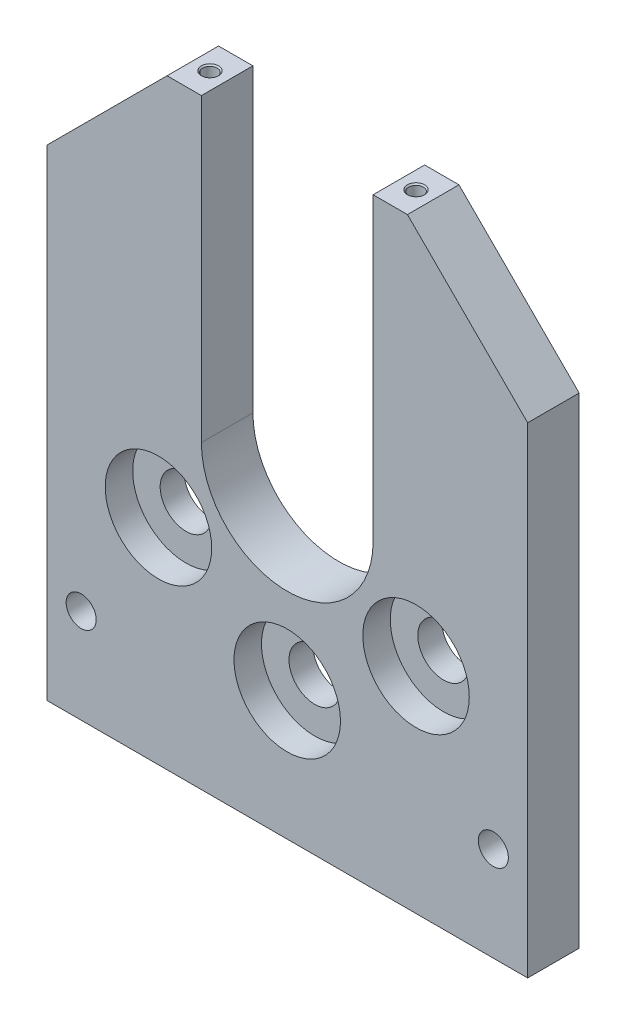
SolidWorks part; units mm, degrees
ref_plane "Front Plane" through (0, 0, 0) normal (0, 0, 1) x (1, 0, 0)
ref_plane "Top Plane" through (0, 0, 0) normal (0, 1, 0) x (1, 0, 0)
ref_plane "Right Plane" through (0, 0, 0) normal (1, 0, 0) x (0, 0, -1)
sketch "Sketch1" plane through (0, 0, 0) normal (0, 1, 0) x (1, 0, 0)
  line L1 (-140, 15) -> (140, 15)
  line L2 (-140, 15) -> (-140, -15)
  line L3 (-140, -15) -> (140, -15)
  line L4 (140, 15) -> (140, -15)
  line L5 (-140, 15) -> (140, -15) construction
  line L6 (-140, -15) -> (140, 15) construction
  point P0 (0, 0)
  dimension "D1" = 280
  dimension "D2" = 30
extrude "Boss-Extrude1" add sketch "Sketch1" along normal blind 350
sketch "Sketch2" plane through (0, 0, 15) normal (0, 0, 1) x (1, 0, 0)
  line L0 (0, 350) -> (0, 175) construction
  line L1 (-140, 350) -> (140, 350) construction
  line L2 (50, 350) -> (50, 175)
  line L3 (-50, 350) -> (-50, 175)
  arc A0 (50, 350) -> (-50, 350) centre (0, 350) ccw
  arc A1 (-50, 175) -> (50, 175) centre (0, 175) ccw
  point P5 (0, 262.5)
  point P10 (0, 125)
  dimension "D1" = 100
  dimension "D2" = 225
extrude "Cut-Extrude1" cut sketch "Sketch2" against normal blind 350
chamfer "Chamfer1" distance 70 angle 45 2 edges at (-140, 350, 0) (140, 350, 0)
sketch "Sketch8" plane through (0, 350, 0) normal (0, 1, 0) x (1, 0, 0)
  point P0 (-60, 0)
  point P1 (60, 0)
  dimension "D1" = 60
  dimension "D2" = 60
hole_wizard "M10 Tapped Hole3" positions "3DSketch4" profile "Sketch10" tap size "M10" standard "ISO"
sketch3d "3DSketch4"
  point P0 (-60, 350, 0)
  point P3 (60, 350, 0)
sketch "Sketch10" plane through (-60, 350, 0) normal (1, 0, 0) x (0, 0, 1)
  line L0 (0, 0) -> (0, 27.0537)
  line L1 (0, 27.0537) -> (4.25, 24.5)
  line L2 (4.25, 24.5) -> (4.25, 0.775)
  line L3 (4.25, 0.775) -> (5.025, 0)
  line L5 (5.025, 0) -> (0, 0)
  line L6 (-4.25, 0.775) -> (-5.025, 0) construction
  line L10 (0, 27.0537) -> (-4.25, 24.5) construction
  line L11 (0, -6.35) -> (0, 107.95) construction
  dimension "Tap Drill Dia." = 8.5
  dimension "Tap Drill Depth" = 24.5
  dimension "Near C'Sink Dia." = 10.05
  dimension "Near C'Sink Angle" = 90
  dimension "Drill Angle" = 118
cosmetic thread "Hole Thread5" parameters "D1"=20, "D2"=10
cosmetic thread "Hole Thread6" parameters "D1"=20, "D2"=10
sketch "Sketch11" plane through (0, 0, 15) normal (0, 0, 1) x (1, 0, 0)
  line L0 (-140, 0) -> (140, 0) construction
  line L1 (-140, 280) -> (-140, 0) construction
  line L2 (140, 280) -> (140, 0) construction
  circle A0 centre (-120, 55) radius 8.75
  circle A1 centre (120, 55) radius 8.75
  point P12 (157.105, 3.5552)
  dimension "D1" = 17.5
  dimension "D4" = 20
  dimension "D2" = 55
  dimension "D3" = 20
  dimension "D5" = 55
extrude "Cut-Extrude3" cut sketch "Sketch11" against normal blind 350
sketch "Sketch12" plane through (0, 0, 15) normal (0, 0, 1) x (1, 0, 0)
  circle A0 centre (-75, 124.7494) radius 15
  circle A1 centre (75, 124.7494) radius 15
  circle A2 centre (0, 75) radius 15
  arc A3 (-50, 175) -> (50, 175) centre (0, 175) ccw construction
  point P6 (0, 0)
  point P11 (0, 125)
  point P12 (0, 0)
  dimension "D1" = 30
  dimension "D2" = 90
  dimension "D3" = 90
  dimension "D4" = 75
  dimension "D5" = 75
  dimension "D6" = 75
extrude "Cut-Extrude4" cut sketch "Sketch12" against normal blind 350
sketch "Sketch13" plane through (0, 0, 15) normal (0, 0, 1) x (1, 0, 0)
  circle A0 centre (-75, 124.7494) radius 31
  circle A1 centre (0, 75) radius 31
  circle A2 centre (75, 124.7494) radius 31
  dimension "D1" = 62
extrude "Cut-Extrude5" cut sketch "Sketch13" against normal blind 16
